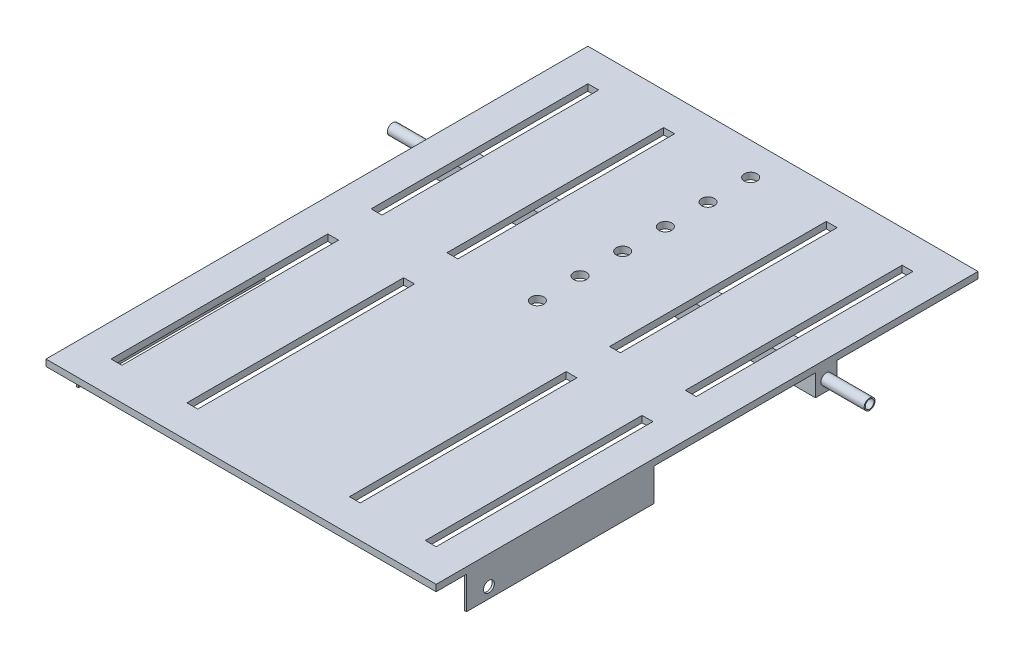
SolidWorks part; units mm, degrees
material "Plain Carbon Steel"
ref_plane "Front Plane" through (0, 0, 0) normal (0, 0, 1) x (1, 0, 0)
ref_plane "Top Plane" through (0, 0, 0) normal (0, 1, 0) x (1, 0, 0)
ref_plane "Right Plane" through (0, 0, 0) normal (1, 0, 0) x (0, 0, -1)
sketch "Sketch1" plane through (0, 0, 0) normal (0, 1, 0) x (1, 0, 0)
  line L1 (-228.6, 317.5) -> (228.6, 317.5)
  line L2 (-228.6, 317.5) -> (-228.6, -317.5)
  line L3 (-228.6, -317.5) -> (228.6, -317.5)
  line L4 (228.6, 317.5) -> (228.6, -317.5)
  line L5 (-228.6, 317.5) -> (228.6, -317.5) construction
  line L6 (-228.6, -317.5) -> (228.6, 317.5) construction
  point P0 (0, 0)
  dimension "D1" = 635
  dimension "D2" = 457.2
extrude "Boss-Extrude1" add sketch "Sketch1" along normal blind 7.62
sketch "Sketch2" plane through (0, 7.62, 0) normal (0, 1, 0) x (1, 0, 0)
  line L0 (228.6, 317.5) -> (-228.6, 317.5) construction
  line L1 (-101.6, 279.4) -> (-88.9, 279.4)
  line L2 (-101.6, 279.4) -> (-101.6, 25.4)
  line L3 (-101.6, 25.4) -> (-88.9, 25.4)
  line L4 (-88.9, 279.4) -> (-88.9, 25.4)
  line L5 (-101.6, -25.4) -> (-88.9, -25.4)
  line L6 (-101.6, -25.4) -> (-101.6, -279.4)
  line L7 (-101.6, -279.4) -> (-88.9, -279.4)
  line L8 (-88.9, -25.4) -> (-88.9, -279.4)
  line L9 (-228.6, 317.5) -> (-228.6, -317.5) construction
  line L12 (-190.5, 279.4) -> (-190.5, 25.4)
  line L13 (-190.5, 279.4) -> (-177.8, 279.4)
  line L14 (-177.8, 279.4) -> (-177.8, 25.4)
  line L15 (-190.5, 25.4) -> (-177.8, 25.4)
  line L16 (-190.5, -25.4) -> (-190.5, -279.4)
  line L17 (-190.5, -25.4) -> (-177.8, -25.4)
  line L18 (-177.8, -25.4) -> (-177.8, -279.4)
  line L19 (-190.5, -279.4) -> (-177.8, -279.4)
  line L20 (177.8, 279.4) -> (177.8, 25.4)
  line L21 (177.8, 279.4) -> (190.5, 279.4)
  line L22 (190.5, 279.4) -> (190.5, 25.4)
  line L23 (177.8, 25.4) -> (190.5, 25.4)
  line L24 (88.9, 279.4) -> (88.9, 25.4)
  line L25 (88.9, 25.4) -> (101.6, 25.4)
  line L26 (101.6, 279.4) -> (101.6, 25.4)
  line L27 (88.9, 279.4) -> (101.6, 279.4)
  line L28 (177.8, -25.4) -> (177.8, -279.4)
  line L29 (177.8, -25.4) -> (190.5, -25.4)
  line L30 (190.5, -25.4) -> (190.5, -279.4)
  line L31 (177.8, -279.4) -> (190.5, -279.4)
  line L32 (88.9, -25.4) -> (88.9, -279.4)
  line L33 (88.9, -279.4) -> (101.6, -279.4)
  line L34 (101.6, -25.4) -> (101.6, -279.4)
  line L35 (88.9, -25.4) -> (101.6, -25.4)
  line L36 (228.6, -317.5) -> (228.6, 317.5) construction
  dimension "D1" = 254
  dimension "D2" = 38.1
  dimension "D3" = 127
  dimension "D4" = 12.7
  dimension "D5" = 50.8
  dimension "D6" = 127
  dimension "D7" = 254
  dimension "D8" = 2
  dimension "D10" = 127
  dimension "D11" = 355.6
  dimension "D9" = 2
extrude "Cut-Extrude1" cut sketch "Sketch2" against normal through all
sketch "Sketch3" plane through (0, 0, 0) normal (0, -1, 0) x (1, 0, 0)
  line L1 (-228.6, 292.1) -> (228.6, 292.1)
  line L2 (-228.6, 292.1) -> (-228.6, 215.9)
  line L3 (-228.6, 215.9) -> (228.6, -5.5321)
  line L4 (228.6, 292.1) -> (228.6, -5.5321)
  line L5 (-228.6, 317.5) -> (228.6, 317.5) construction
  line L6 (228.6, 317.5) -> (228.6, -317.5) construction
  line L7 (-228.6, -317.5) -> (-228.6, 317.5) construction
  dimension "D1" = 76.2
  dimension "D2" = 25.4
  dimension "D3" = 508
sketch "Sketch5" plane through (228.6, 0, 0) normal (1, 0, 0) x (0, 0, -1)
  line L0 (127, 0) -> (127, -25.4)
  line L1 (-317.5, 0) -> (317.5, 0) construction
  line L2 (127, -25.4) -> (152.4, -25.4)
  line L3 (152.4, -25.4) -> (152.4, 0)
  line L4 (127, 0) -> (152.4, 0)
  dimension "D1" = 25.4
  dimension "D2" = 25.4
  dimension "D3" = 127
extrude "Boss-Extrude3" add sketch "Sketch5" against normal up to surface (228.6 mm away) up to plane "Right Plane"
sketch "Sketch6" plane through (228.6, 0, 0) normal (1, 0, 0) x (0, 0, -1)
  line L0 (139.7, -25.4) -> (139.7, -12.7) construction
  line L1 (127, -25.4) -> (152.4, -25.4) construction
  circle A0 centre (139.7, -12.7) radius 6.35
  dimension "D1" = 12.7
  dimension "D2" = 12.7
extrude "Boss-Extrude4" add sketch "Sketch6" along normal blind 50.8
extrude "Boss-Extrude6" add sketch "Sketch3" along normal blind 38.1
mirror "Mirror2" about plane through (0, 0, 0) normal (1, 0, 0) of "Boss-Extrude4", "Boss-Extrude3"
sketch "Sketch7" plane through (0, -38.1, 0) normal (0, -1, 0) x (1, 0, 0)
  line L4 (-228.6, 215.9) -> (228.6, -5.5321) construction
  line L5 (-226.06, 214.6698) -> (226.06, -4.3019)
  line L8 (-226.06, 289.56) -> (-226.06, 217.492)
  line L9 (-226.06, 217.492) -> (226.06, -1.4797)
  line L10 (226.06, -1.4797) -> (226.06, 289.56)
  line L11 (226.06, 289.56) -> (-226.06, 289.56)
  line L12 (-226.06, 289.56) -> (-226.06, 214.6698)
  line L14 (226.06, -4.3019) -> (226.06, 289.56)
  line L15 (226.06, 289.56) -> (-226.06, 289.56)
  dimension "D1" = 2.54
extrude "Cut-Extrude2" cut sketch "Sketch7" against normal up to surface (38.1 mm away) and the other way through all up to face at (-23.0188, 0, -9.4048)
sketch "Sketch8" plane through (-228.6, 0, 0) normal (-1, 0, 0) x (0, 0, 1)
  line L0 (215.9, -38.1) -> (215.9, 0) construction
  line L1 (215.9, 0) -> (63.5, 0)
  line L2 (215.9, 0) -> (215.9, -38.1)
  line L3 (215.9, -38.1) -> (63.5, -38.1)
  line L4 (63.5, 0) -> (63.5, -38.1)
  line L5 (-127, 0) -> (215.9, 0) construction
  dimension "D1" = 152.4
  dimension "D2" = 38.1
extrude "Boss-Extrude7" add sketch "Sketch8" against normal blind 2.54
sketch "Sketch9" plane through (0, 0, 292.1) normal (0, 0, 1) x (1, 0, 0)
  line L4 (228.6, 0) -> (-228.6, 0)
  line L5 (-228.6, 0) -> (-228.6, -38.1)
  line L6 (-228.6, -38.1) -> (228.6, -38.1)
  line L7 (228.6, -38.1) -> (228.6, 0)
  line L8 (228.6, 0) -> (-228.6, 0)
  line L9 (-228.6, 0) -> (-228.6, -38.1)
  line L10 (-228.6, -38.1) -> (228.6, -38.1)
  line L11 (228.6, -38.1) -> (228.6, 0)
  dimension "D1" = 0
extrude "Cut-Extrude3" cut sketch "Sketch9" against normal blind 10.16
sketch "Sketch10" plane through (-228.6, 0, 0) normal (-1, 0, 0) x (0, 0, 1)
  circle A0 centre (255.6186, -25.7092) radius 6.35
extrude "Cut-Extrude4" cut sketch "Sketch10" against normal through all and the other way through all
sketch "Sketch11" plane through (279.4, 0, 0) normal (1, 0, 0) x (0, 0, -1)
  circle A2 centre (139.7, -12.7) radius 5.08
  circle A3 centre (139.7, -12.7) radius 5.08
  dimension "D1" = 1.27
extrude "Cut-Extrude5" cut sketch "Sketch11" against normal blind 25.4
mirror "Mirror3" about plane through (0, 0, 0) normal (1, 0, 0) of "Cut-Extrude5"
sketch "Sketch12" plane through (226.06, 0, 0) normal (-1, 0, 0) x (0, 0, 1)
  line L0 (-5.5321, -38.1) -> (-5.5321, 0) construction
  line L1 (62.2698, 0) -> (-5.5321, 0)
  line L2 (62.2698, 0) -> (62.2698, -38.1)
  line L3 (62.2698, -38.1) -> (-5.5321, -38.1)
  line L4 (-5.5321, 0) -> (-5.5321, -38.1)
  line L5 (-4.3019, 0) -> (281.94, 0) construction
  dimension "D1" = 66.5717
  dimension "D2" = 38.1
extrude "Cut-Extrude7" cut sketch "Sketch12" against normal through all
sketch "Sketch15" plane through (0, 0, 0) normal (0, -1, 0) x (1, 0, 0)
  circle A0 centre (0, -229.7271) radius 1052.774
sketch "Sketch16" plane through (0, 0, 0) normal (0, -1, 0) x (1, 0, 0)
  circle A0 centre (0, -229.7271) radius 7.5
  dimension "D1" = 15
extrude "Cut-Extrude9" cut sketch "Sketch16" against normal through all
pattern_linear "LPattern1" count 5 spacing 50 along (0, 0, 1) of "Cut-Extrude9"
pattern_linear "LPattern2" count 3 spacing 50 along (0, 0, -1) of "Cut-Extrude9"
